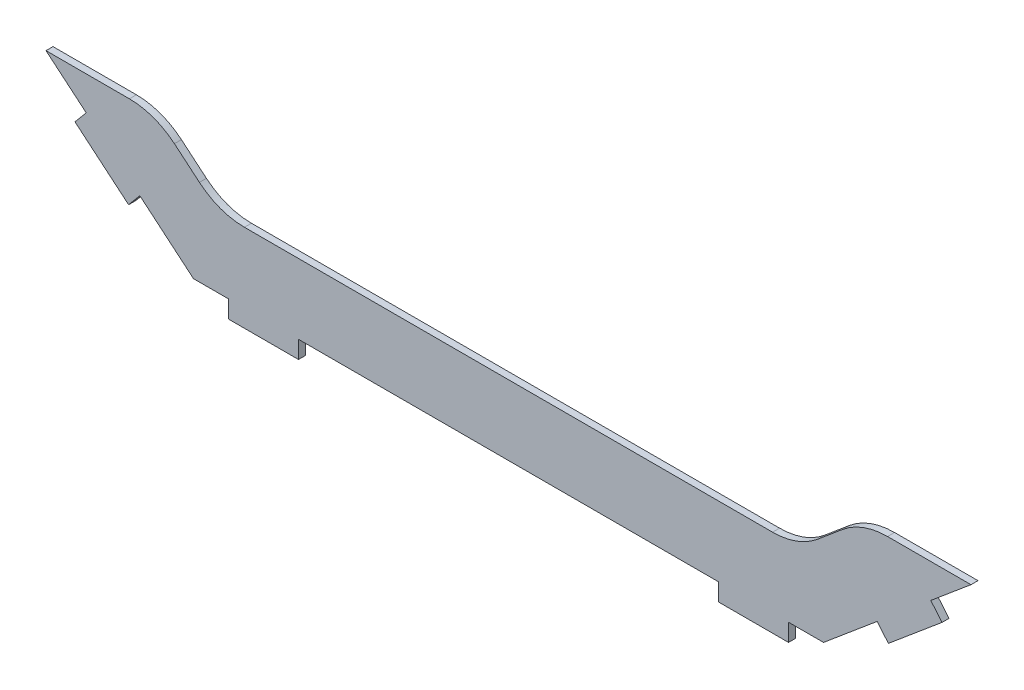
SolidWorks part; units mm, degrees
material "PBT General Purpose"
ref_plane "Front Plane" through (0, 0, 0) normal (0, 0, 1) x (1, 0, 0)
ref_plane "Top Plane" through (0, 0, 0) normal (0, 1, 0) x (1, 0, 0)
ref_plane "Right Plane" through (0, 0, 0) normal (1, 0, 0) x (0, 0, -1)
sketch "frame_outline" plane through (0, 0, 0) normal (0, 0, 1) x (1, 0, 0)
  line L89 (0, 0) -> (3, 0)
  line L99 (3, 0) -> (3, -0.25)
  line L100 (3, -0.25) -> (4, -0.25)
  line L101 (4, -0.25) -> (4, 0)
  line L102 (4, 0) -> (4.5, 0)
  line L103 (4.5, 0) -> (5.266, 0.6428)
  line L104 (5.266, 0.6428) -> (5.4267, 0.4513)
  line L105 (5.4267, 0.4513) -> (6.1928, 1.0941)
  line L106 (6.1928, 1.0941) -> (6.0321, 1.2856)
  line L107 (6.0321, 1.2856) -> (6.6066, 1.7677)
  line L108 (6.6066, 1.7677) -> (5.0509, 1.7677)
  line L109 (5.0509, 1.7677) -> (4.136, 1)
  line L110 (4.136, 1) -> (-4.136, 1)
  line L111 (0, 0) -> (-3, 0)
  line L112 (-3, 0) -> (-3, -0.25)
  line L113 (-3, -0.25) -> (-4, -0.25)
  line L114 (-4, -0.25) -> (-4, 0)
  line L115 (-4, 0) -> (-4.5, 0)
  line L116 (-4.5, 0) -> (-5.266, 0.6428)
  line L117 (-5.266, 0.6428) -> (-5.4267, 0.4513)
  line L118 (-5.4267, 0.4513) -> (-6.1928, 1.0941)
  line L119 (-6.1928, 1.0941) -> (-6.0321, 1.2856)
  line L120 (-6.0321, 1.2856) -> (-6.6066, 1.7677)
  line L121 (-6.6066, 1.7677) -> (-5.0509, 1.7677)
  line L122 (-5.0509, 1.7677) -> (-4.136, 1)
  dimension "D1" = 3
  dimension "D2" = 1
  dimension "D3" = 0.5
  dimension "D4" = 1
  dimension "D5" = 0.25
  dimension "D6" = 0.25
  dimension "D7" = 0.25
  dimension "D8" = 140
  dimension "D9" = 1
  dimension "D10" = 140
  dimension "D11" = 1
  dimension "D12" = 0.75
  dimension "D13" = 1
  dimension "D14" = 1
extrude "Boss-Extrude1" add sketch "frame_outline" along normal mid plane 0.1
fillet "Fillet1" radius 1 4 edges at (4.136, 1, 0) (5.0509, 1.7677, 0) (-4.136, 1, 0) (-5.0509, 1.7677, 0)
equation "\"t\"= 0.25'thickness of the sheets"
equation "\"t_cf\" = 0.115'thickness of single carbon fiber layer"
equation "\"t_kapton\" = 0.025'thickness of single Kapton flex layer"
equation "\"t_fr4\" = 0.1'thickness of FR4 with copper layer"
equation "\"joint_flex\"= 0.1'Width of flextures gap"
equation "\"joint_flex_eff\"= 0.02'Width of flecture after castelation"
equation "\"joint_fold\"= 0.2'Width of folding joints for 90deg fold"
equation "\"gap_tolerance\"= 0.002'Width to have interfecence fit between carbon fiber inserts"
equation "\"assemble_angle\"= 90'Angle of assembly parts"
equation "\"D1@Boss-Extrude1\"=0.1"
equation "\"link_lift\"= 0.5'Actuation linkage amplification for the lift motion"
equation "\"link_swing\"= 0.45'Actuation linkage amplification for the swing motion"
